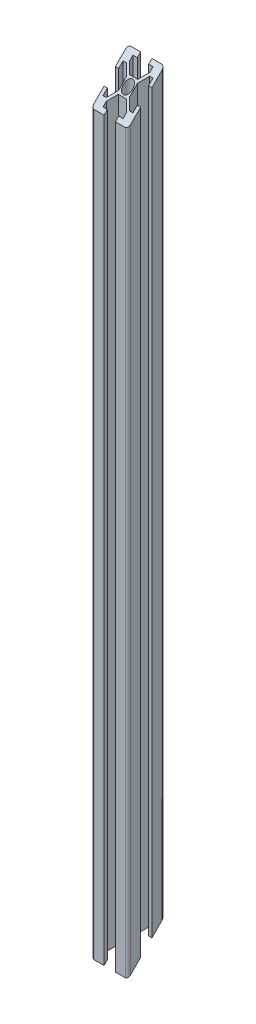
SolidWorks part; units mm, degrees
ref_plane "前视基准面" through (0, 0, 0) normal (0, 0, 1) x (1, 0, 0)
ref_plane "上视基准面" through (0, 0, 0) normal (0, 1, 0) x (1, 0, 0)
ref_plane "右视基准面" through (0, 0, 0) normal (1, 0, 0) x (0, 0, -1)
sketch "草图1" plane through (0, 0, 0) normal (0, 1, 0) x (1, 0, 0)
  line L0 (-8.656, -4.948) -> (-6.856, -4.948)
  line L1 (-7.156, 8.152) -> (9.844, 8.152)
  line L2 (-8.656, 6.652) -> (-8.656, -10.348)
  line L3 (-7.156, -11.848) -> (9.844, -11.848)
  line L4 (11.344, 6.652) -> (11.344, -10.348)
  line L5 (-8.656, 8.152) -> (11.344, -11.848) construction
  line L6 (-8.656, -11.848) -> (11.344, 8.152) construction
  line L7 (-1.7101, 1.252) -> (4.3981, 1.252)
  line L8 (-1.7101, 1.252) -> (-1.7101, -4.948)
  line L9 (-1.7101, -4.948) -> (4.3981, -4.948)
  line L10 (4.3981, 1.252) -> (4.3981, -4.948)
  line L11 (-1.7101, 1.252) -> (4.3981, -4.948) construction
  line L12 (-1.7101, -4.948) -> (4.3981, 1.252) construction
  line L13 (-6.856, -4.948) -> (-6.856, -7.348)
  line L14 (-6.856, -7.348) -> (-5.0531, -7.348)
  line L15 (-5.0531, -7.348) -> (-1.7101, -4.0051)
  line L16 (-4.156, 4.5491) -> (-0.8131, 1.2061)
  line L17 (-4.156, 6.352) -> (-4.156, 4.5491)
  line L18 (-1.756, 6.352) -> (-4.156, 6.352)
  line L19 (-1.756, 8.152) -> (-1.756, 6.352)
  line L20 (7.741, 3.652) -> (4.3981, 0.3091)
  line L21 (9.544, 3.652) -> (7.741, 3.652)
  line L22 (9.544, 1.252) -> (9.544, 3.652)
  line L23 (11.344, 1.252) -> (9.544, 1.252)
  line L24 (6.844, -8.245) -> (3.5011, -4.9021)
  line L25 (6.844, -10.048) -> (6.844, -8.245)
  line L26 (4.444, -10.048) -> (6.844, -10.048)
  line L27 (4.444, -11.848) -> (4.444, -10.048)
  line L28 (-1.756, -11.848) -> (-1.756, -10.048)
  line L29 (-1.756, -10.048) -> (-4.156, -10.048)
  line L30 (-4.156, -10.048) -> (-4.156, -8.245)
  line L31 (-4.156, -8.245) -> (-0.8131, -4.9021)
  line L32 (-6.856, 3.652) -> (-5.0531, 3.652)
  line L33 (-5.0531, 3.652) -> (-1.7101, 0.3091)
  line L34 (-6.856, 1.252) -> (-6.856, 3.652)
  line L35 (-8.656, 1.252) -> (-6.856, 1.252)
  line L36 (6.844, 6.352) -> (6.844, 4.5491)
  line L37 (6.844, 4.5491) -> (3.5011, 1.2061)
  line L38 (4.444, 6.352) -> (6.844, 6.352)
  line L39 (4.444, 8.152) -> (4.444, 6.352)
  line L40 (9.544, -7.348) -> (7.741, -7.348)
  line L41 (7.741, -7.348) -> (4.3981, -4.0051)
  line L42 (9.544, -4.948) -> (9.544, -7.348)
  line L43 (11.344, -4.948) -> (9.544, -4.948)
  circle A0 centre (1.344, -1.848) radius 2.5
  arc A1 (-8.656, 6.652) -> (-7.156, 8.152) centre (-7.156, 6.652) cw
  arc A2 (-8.656, -10.348) -> (-7.156, -11.848) centre (-7.156, -10.348) ccw
  arc A3 (9.844, 8.152) -> (11.344, 6.652) centre (9.844, 6.652) cw
  arc A4 (11.344, -10.348) -> (9.844, -11.848) centre (9.844, -10.348) cw
  point P0 (1.344, -1.848)
  point P19 (1.344, -1.848)
  point P25 (1.344, -1.848)
  point P31 (1.344, -1.848)
  point P37 (1.344, -1.848)
  point P59 (1.344, -1.848)
extrude "凸台-拉伸1" add sketch "草图1" along normal blind 423.22
sketch "草图3" plane through (-8.656, 0, 0) normal (-1, 0, 0) x (0, 0, 1)
  line L0 (-8.152, 423.22) -> (11.848, 403.22)
  line L1 (11.848, 423.22) -> (11.848, 0) construction
  line L2 (11.848, 0) -> (-8.152, 20)
  line L3 (-8.152, 423.22) -> (-8.152, 0) construction
  line L4 (-8.152, 20) -> (-8.152, 0)
  line L5 (-8.152, 0) -> (11.848, 0)
  line L6 (-8.152, 423.22) -> (11.848, 423.22)
  line L7 (11.848, 423.22) -> (11.848, 403.22)
  dimension "D1" = 45
  dimension "D2" = 45
extrude "切除-拉伸2" cut sketch "草图3" against normal through all
